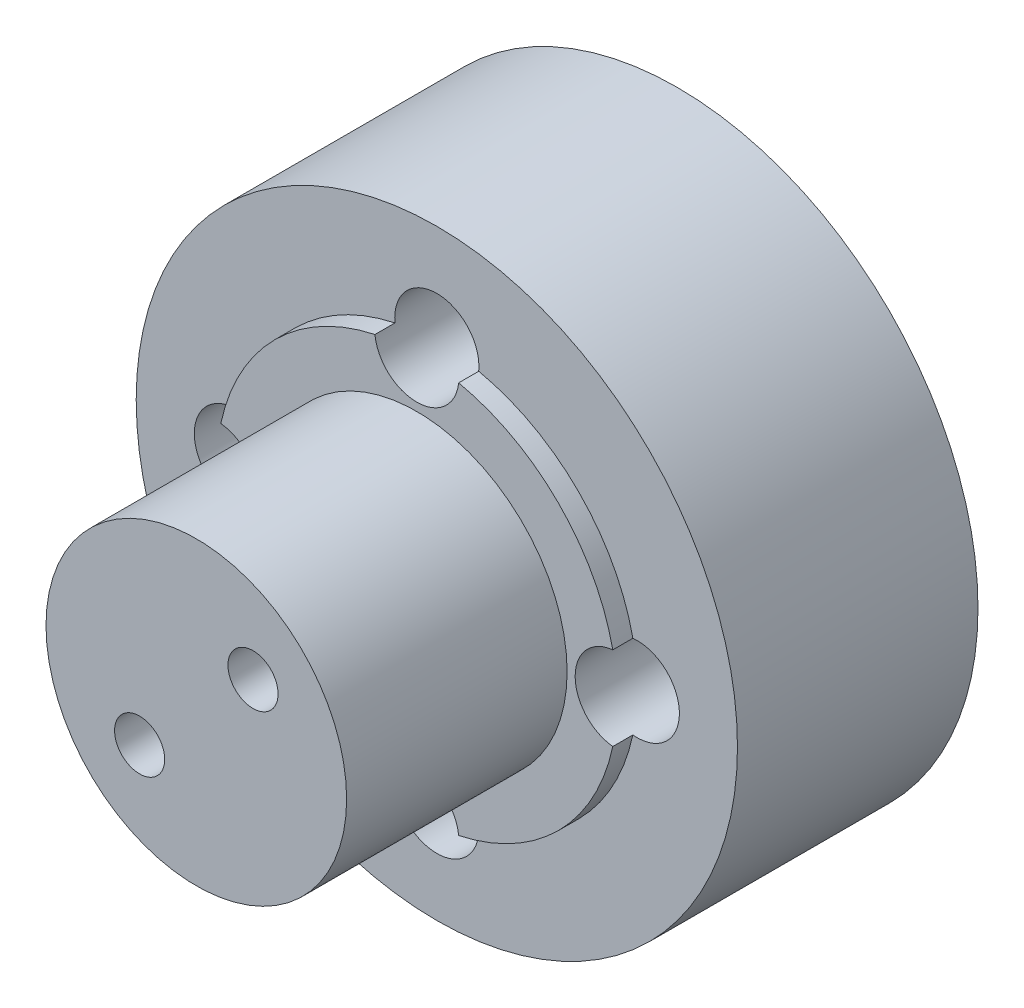
SolidWorks part; units mm, degrees
ref_plane "Спереди" through (0, 0, 0) normal (0, 0, 1) x (1, 0, 0)
ref_plane "Сверху" through (0, 0, 0) normal (0, 1, 0) x (1, 0, 0)
ref_plane "Справа" through (0, 0, 0) normal (1, 0, 0) x (0, 0, -1)
sketch "Эскиз1" plane through (0, 0, 0) normal (0, 0, 1) x (1, 0, 0)
  circle A0 centre (0, 0) radius 15
  dimension "D1" = 30
extrude "Бобышка-Вытянуть1" add sketch "Эскиз1" along normal blind 12
sketch "Эскиз2" plane through (0, 0, 12) normal (0, 0, 1) x (1, 0, 0)
  circle A0 centre (0, 0) radius 10
  dimension "D1" = 20
extrude "Бобышка-Вытянуть2" add sketch "Эскиз2" along normal blind 1
sketch "Эскиз3" plane through (0, 0, 13) normal (0, 0, 1) x (1, 0, 0)
  circle A0 centre (0, 0) radius 7.5
  dimension "D1" = 15
extrude "Бобышка-Вытянуть3" add sketch "Эскиз3" along normal blind 11
sketch "Эскиз4" plane through (0, 0, 0) normal (0, 0, -1) x (-1, 0, 0)
  line L0 (0, 15) -> (0, -15) construction
  line L1 (-15, 0) -> (15, 0) construction
  circle A0 centre (0, 0) radius 15 construction
  circle A1 centre (0, 0) radius 10 construction
  dimension "D1" = 20
hole_wizard "Отверстие обработанное метчиком M5x0.81" positions "Эскиз6" profile "Эскиз5" tap size "M5x0.8" standard "Ansi Metric" end condition through all
sketch "Эскиз6" plane through (0, 0, 0) normal (0, 0, -1) x (-1, 0, 0)
  line L0 (0, 15) -> (0, -15) construction
  line L1 (-15, 0) -> (15, 0) construction
  circle A0 centre (0, 0) radius 10 construction
  point P0 (0, 10)
  point P6 (10, 0)
  point P10 (-10, 0)
  point P12 (0, -10)
sketch "Эскиз5" plane through (0, 10, 0) normal (1, 0, 0) x (0, 1, 0)
  line L0 (0, 0) -> (0, 24)
  line L1 (0, 24) -> (2.1, 24)
  line L2 (2.1, 24) -> (2.1, 0)
  line L5 (2.1, 0) -> (0, 0)
  line L11 (0, -6.35) -> (0, 107.95) construction
  dimension "Диаметр проходного сверла" = 4.2
  dimension "Глубина проходного сверла" = 24
cosmetic thread "Отверстие резьбы1" parameters "D2"=5
cosmetic thread "Отверстие резьбы2" parameters "D2"=5
cosmetic thread "Отверстие резьбы3" parameters "D2"=5
cosmetic thread "Отверстие резьбы4" parameters "D2"=5
sketch "Эскиз7" plane through (0, 0, 24) normal (0, 0, 1) x (1, 0, 0)
  line L0 (2.8284, 2.8284) -> (-2.8284, -2.8284) construction
  line L1 (15, 0) -> (-15, 0) construction
  line L2 (-2.8284, 2.8284) -> (2.8284, -2.8284) construction
  circle A0 centre (0, 0) radius 4 construction
  dimension "D1" = 8
  dimension "D2" = 45
hole_wizard "Отверстие обработанное метчиком M3x0.51" positions "Эскиз9" profile "Эскиз8" tap size "M3x0.5" standard "Ansi Metric" end condition through all
sketch "Эскиз9" plane through (0, 0, 24) normal (0, 0, 1) x (1, 0, 0)
  point P0 (-2.8284, -2.8284)
  point P3 (2.8284, 2.8284)
sketch "Эскиз8" plane through (-2.8284, -2.8284, 24) normal (1, 0, 0) x (0, -1, 0)
  line L0 (0, 0) -> (0, 24)
  line L1 (0, 24) -> (1.25, 24)
  line L2 (1.25, 24) -> (1.25, 0)
  line L5 (1.25, 0) -> (0, 0)
  line L11 (0, -6.35) -> (0, 107.95) construction
  dimension "Диаметр проходного сверла" = 2.5
  dimension "Глубина проходного сверла" = 24
cosmetic thread "Отверстие резьбы5" parameters "D2"=3
cosmetic thread "Отверстие резьбы6" parameters "D2"=3
